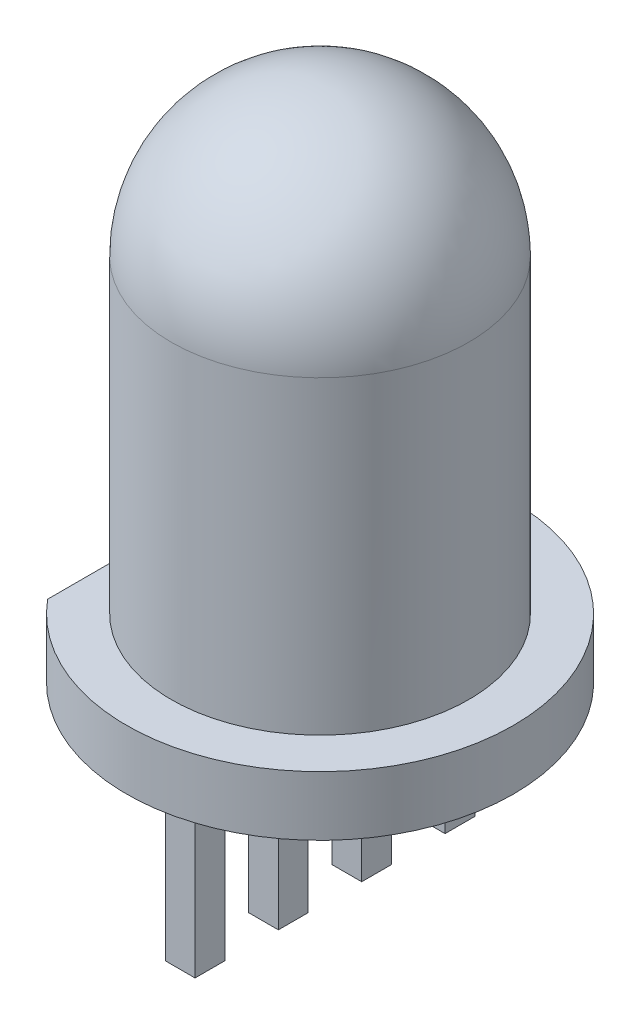
SolidWorks part; units mm, degrees
ref_plane "Front" through (0, 0, 0) normal (0, 0, 1) x (1, 0, 0)
ref_plane "Top" through (0, 0, 0) normal (0, 1, 0) x (1, 0, 0)
ref_plane "Right" through (0, 0, 0) normal (1, 0, 0) x (0, 0, -1)
sketch "Эскиз1" plane through (0, 0, 0) normal (1, 0, 0) x (0, 0, -1)
  line L0 (0, -2.6033) -> (0, 12.5474) construction
  line L1 (-3.25, 0) -> (0, 0)
  line L2 (-3.25, 0) -> (-3.25, 1)
  line L3 (-3.25, 1) -> (0, 1)
  line L4 (-2.5, 1) -> (-2.5, 6.2)
  line L5 (0, 8.7) -> (0, 0)
  arc A0 (-2.5, 6.2) -> (0, 8.7) centre (0, 6.2) cw
  dimension "D3" = 1
  dimension "D1" = 8.7
  dimension "D2" = 5
  dimension "D4" = 6.5
revolve "Повернуть1" add sketch "Эскиз1" angle 360 about L0
sketch "Эскиз4" plane through (0, 1, 0) normal (0, 1, 0) x (1, 0, 0)
  line L0 (-2.5, 2.0767) -> (-2.5, -2.0767)
  circle A0 centre (0, 0) radius 2.5 construction
  circle A1 centre (0, 0) radius 3.25 construction
  arc A3 (-2.5, 2.0767) -> (-2.5, -2.0767) centre (0, 0) ccw
extrude "Вырез-Вытянуть2" cut sketch "Эскиз4" against normal up to next
sketch "Эскиз5" plane through (0, 0, 0) normal (0, -1, 0) x (1, 0, 0)
  line L0 (-0.25, 0.45) -> (0.25, 0.45)
  line L1 (-0.25, 2.35) -> (0.25, 2.35)
  line L2 (-0.25, 2.35) -> (-0.25, 1.85)
  line L3 (-0.25, 1.85) -> (0.25, 1.85)
  line L4 (0.25, 2.35) -> (0.25, 1.85)
  line L5 (0, 1.85) -> (0, 2.35) construction
  line L6 (-0.25, 2.1) -> (0.25, 2.1) construction
  line L7 (-0.25, 0.95) -> (-0.25, 0.45)
  line L8 (-0.25, 0.95) -> (0.25, 0.95)
  line L9 (0.25, 0.95) -> (0.25, 0.45)
  line L10 (-0.25, -0.95) -> (0.25, -0.95)
  line L11 (-0.25, -0.45) -> (-0.25, -0.95)
  line L12 (-0.25, -0.45) -> (0.25, -0.45)
  line L13 (0.25, -0.45) -> (0.25, -0.95)
  line L14 (-0.25, -2.35) -> (0.25, -2.35)
  line L15 (-0.25, -1.85) -> (-0.25, -2.35)
  line L16 (-0.25, -1.85) -> (0.25, -1.85)
  line L17 (0.25, -1.85) -> (0.25, -2.35)
  point P272 (0, 2.1)
  dimension "D1" = 0.5
  dimension "D2" = 0.5
  dimension "D3" = 2.1
  dimension "D4" = 4
extrude "Бобышка-Вытянуть1" add sketch "Эскиз5" along normal blind 3
